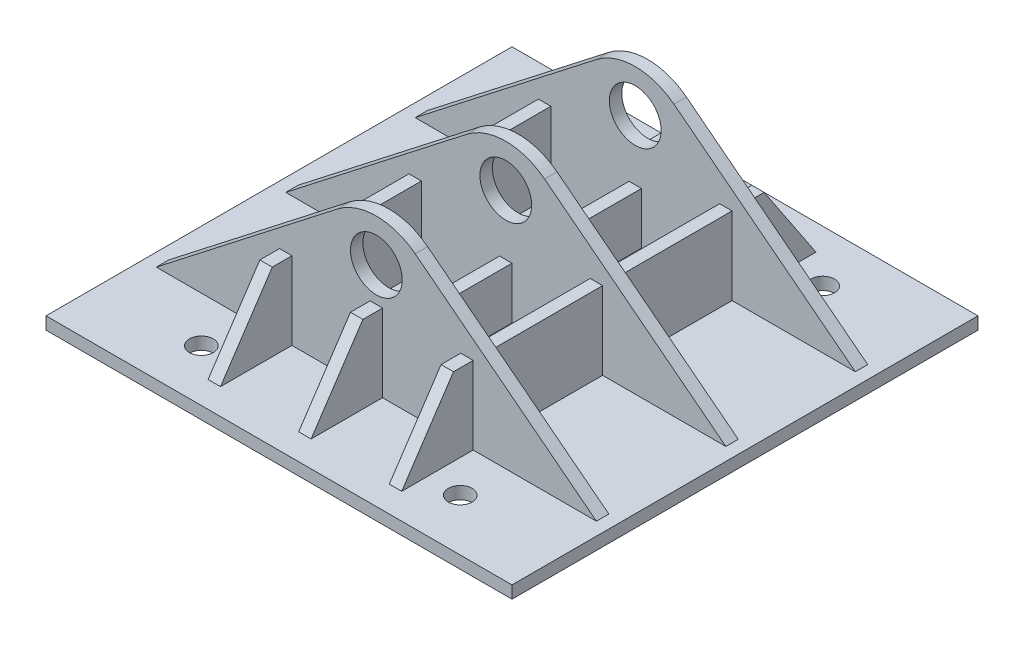
SolidWorks part; units mm, degrees
ref_plane "前视基准面" through (0, 0, 0) normal (0, 0, 1) x (1, 0, 0)
ref_plane "上视基准面" through (0, 0, 0) normal (0, 1, 0) x (1, 0, 0)
ref_plane "右视基准面" through (0, 0, 0) normal (1, 0, 0) x (0, 0, -1)
sketch "草图1" plane through (0, 0, 0) normal (0, 1, 0) x (1, 0, 0)
  line L1 (0, 0) -> (450, 0)
  line L2 (0, 0) -> (0, 450)
  line L3 (0, 450) -> (450, 450)
  line L4 (450, 0) -> (450, 450)
  dimension "D1" = 450
extrude "凸台-拉伸1" add sketch "草图1" along normal blind 12
sketch "草图2" plane through (0, 12, 0) normal (0, 1, 0) x (1, 0, 0)
  line L0 (450, 0) -> (450, 450) construction
  line L1 (450, 450) -> (0, 450) construction
  line L2 (-550, 225) -> (49450, 225) construction
  line L3 (225, -550) -> (225, 49450) construction
  line L4 (0, 0) -> (450, 0) construction
  line L5 (0, 450) -> (0, 0) construction
  circle A0 centre (100, 50) radius 11.5
  circle A1 centre (100, 400) radius 11.5
  circle A2 centre (350, 400) radius 11.5
  circle A3 centre (350, 50) radius 11.5
  point P9 (450, 225)
  point P12 (225, 450)
  dimension "D1" = 23
  dimension "D2" = 100
  dimension "D3" = 50
extrude "切除-拉伸1" cut sketch "草图2" against normal through all
sketch "草图5" plane through (0, 12, 0) normal (0, 1, 0) x (1, 0, 0)
  line L0 (0, 450) -> (0, 0) construction
  line L1 (0, 356) -> (450, 356)
  line L2 (0, 356) -> (0, 344)
  line L3 (0, 344) -> (450, 344)
  line L4 (450, 356) -> (450, 344)
  line L5 (450, 0) -> (450, 450) construction
  line L6 (-1000, 225) -> (49000, 225) construction
  line L7 (0, 231) -> (450, 231)
  line L8 (0, 231) -> (0, 219)
  line L9 (0, 219) -> (450, 219)
  line L10 (450, 231) -> (450, 219)
  line L11 (0, 106) -> (450, 106)
  line L12 (0, 106) -> (0, 94)
  line L13 (0, 94) -> (450, 94)
  line L14 (450, 106) -> (450, 94)
  line L15 (-926.1956, 350) -> (49073.8044, 350) construction
  point P19 (0, 225)
  dimension "D1" = 12
  dimension "D2" = 12
  dimension "D3" = 12
  dimension "D4" = 125
extrude "凸台-拉伸2" add sketch "草图5" along normal blind 150
sketch "草图6" plane through (0, 0, -94) normal (0, 0, 1) x (1, 0, 0)
  line L0 (0, 162) -> (0, 12)
  line L1 (0, 12) -> (12.5, 12)
  line L2 (0, 12) -> (450, 12) construction
  line L3 (12.5, 12) -> (187.5, 148.1319)
  line L5 (0, 0) -> (450, 0) construction
  line L6 (262.5, 148.1319) -> (437.5, 12)
  line L7 (0, 12) -> (450, 12) construction
  line L8 (437.5, 12) -> (450, 12)
  line L9 (450, 12) -> (450, 162)
  line L10 (-576.5705, 161) -> (49423.4295, 161) construction
  line L11 (225, -988) -> (225, 49012) construction
  line L12 (0, 162) -> (450, 162) construction
  line L13 (0, 162) -> (450, 162)
  circle A0 centre (225, 120) radius 25
  arc A1 (187.5, 148.1319) -> (262.5, 148.1319) centre (225, 99.925) cw
  point P21 (225, 12)
  dimension "D3" = 50
  dimension "D1" = 75
  dimension "D2" = 12.5
  dimension "D4" = 120
  dimension "D5" = 1
extrude "切除-拉伸2" cut sketch "草图6" against normal through all
sketch "草图7" plane through (0, 0, 0) normal (0, 0, 1) x (1, 0, 0)
  line L0 (225, -875) -> (225, 49125) construction
  line L1 (219, 87) -> (219, 12)
  line L2 (12.5, 12) -> (437.5, 12) construction
  line L3 (219, 12) -> (231, 12)
  line L4 (231, 12) -> (231, 87)
  line L5 (0, 12) -> (450, 12) construction
  line L6 (131.5, 87) -> (143.5, 87)
  line L7 (131.5, 87) -> (131.5, 12)
  line L8 (131.5, 12) -> (143.5, 12)
  line L9 (143.5, 87) -> (143.5, 12)
  line L10 (306.5, 87) -> (318.5, 87)
  line L11 (306.5, 87) -> (306.5, 12)
  line L12 (306.5, 12) -> (318.5, 12)
  line L13 (318.5, 87) -> (318.5, 12)
  line L14 (137.5, -938.1111) -> (137.5, 49061.8889) construction
  line L15 (312.5, -940.2317) -> (312.5, 49059.7683) construction
  line L16 (219, 87) -> (231, 87)
  line L17 (225, -875) -> (225, 49125) construction
  dimension "D1" = 12
  dimension "D2" = 175
  dimension "D3" = 75
extrude "凸台-拉伸3" add sketch "草图7" against normal blind 450
sketch "草图9" plane through (131.5, 0, 0) normal (-1, 0, 0) x (0, 0, 1)
  line L0 (-450, 87) -> (-375, 87)
  line L1 (-450, 87) -> (-356, 87) construction
  line L2 (-375, 87) -> (-425, 12)
  line L3 (-450, 12) -> (0, 12) construction
  line L4 (-425, 12) -> (-450, 12)
  line L5 (-450, 12) -> (-450, 87)
  line L6 (0, 87) -> (-75, 87)
  line L7 (-94, 87) -> (0, 87) construction
  line L8 (-75, 87) -> (-25, 12)
  line L9 (-94, 12) -> (0, 12) construction
  line L10 (-25, 12) -> (0, 12)
  line L11 (0, 12) -> (0, 87)
  dimension "D1" = 25
  dimension "D2" = 75
extrude "切除-拉伸4" cut sketch "草图9" against normal through all
sketch "草图10" plane through (231, 0, 0) normal (1, 0, 0) x (0, 0, -1)
  line L1 (219, 12) -> (219, 148.1319) construction
  line L2 (106, 87) -> (106, 62)
  line L3 (106, 62) -> (219, 62)
  line L4 (219, 87) -> (219, 62)
  line L5 (219, 12) -> (219, 148.1319) construction
  line L6 (344, 87) -> (344, 12) construction
  line L7 (231, 87) -> (344, 87)
  line L8 (231, 87) -> (231, 62)
  line L9 (231, 62) -> (344, 62)
  line L10 (344, 87) -> (344, 62)
  line L11 (106, 87) -> (219, 87)
  line L12 (106, 12) -> (106, 87) construction
  dimension "D1" = 25
extrude "切除-拉伸5" cut sketch "草图10" against normal blind 12
